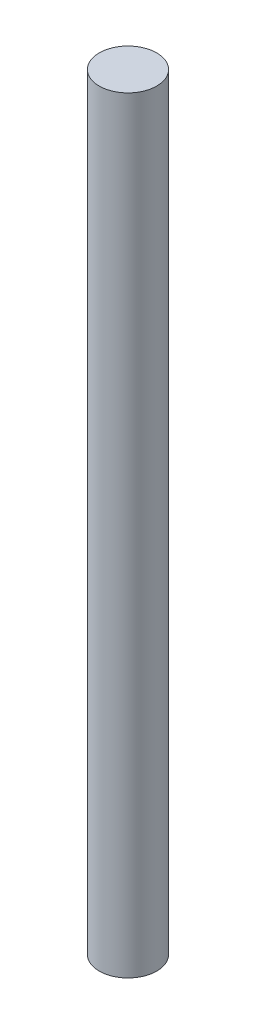
SolidWorks part; units mm, degrees
ref_plane "Plan de face" through (0, 0, 0) normal (0, 0, 1) x (1, 0, 0)
ref_plane "Plan de dessus" through (0, 0, 0) normal (0, 1, 0) x (1, 0, 0)
ref_plane "Plan de droite" through (0, 0, 0) normal (1, 0, 0) x (0, 0, -1)
sketch "Esquisse1" plane through (0, 0, 0) normal (0, 1, 0) x (1, 0, 0)
  circle A0 centre (0, 0) radius 3
  dimension "D1" = 6
extrude "Boss.-Extru.1" add sketch "Esquisse1" along normal blind 80
